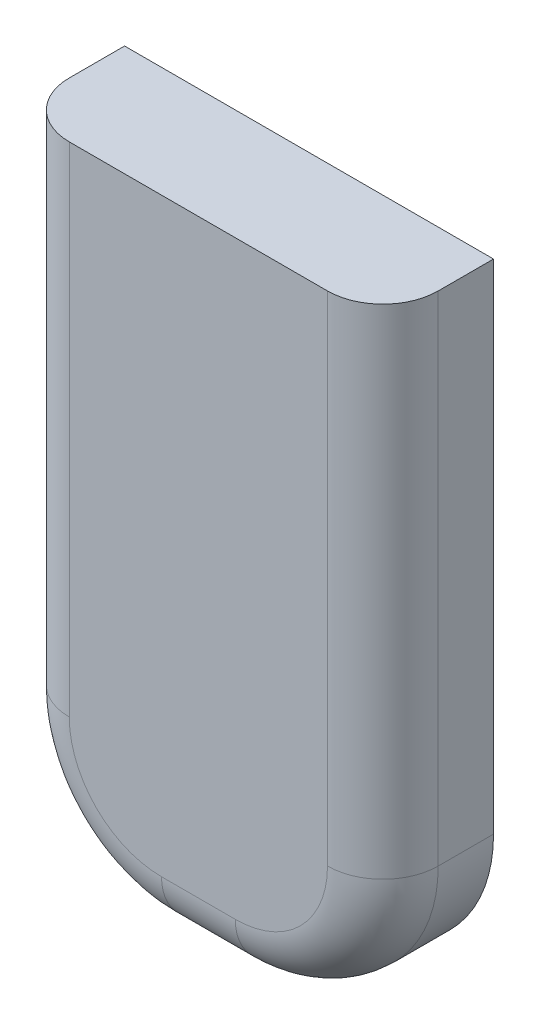
SolidWorks part; units mm, degrees
ref_plane "Front Plane" through (0, 0, 0) normal (0, 0, 1) x (1, 0, 0)
ref_plane "Top Plane" through (0, 0, 0) normal (0, 1, 0) x (1, 0, 0)
ref_plane "Right Plane" through (0, 0, 0) normal (1, 0, 0) x (0, 0, -1)
sketch "Sketch1" plane through (0, 0, 0) normal (0, 0, 1) x (1, 0, 0)
  line L0 (18.5859, -140) -> (118.5859, -140) construction
  line L1 (58.5859, -125) -> (78.5859, -125)
  line L2 (58.5859, -125) -> (58.5859, -152)
  line L3 (66.5859, -160) -> (70.5859, -160)
  line L4 (78.5859, -125) -> (78.5859, -152)
  line L5 (68.5859, -300) -> (68.5859, -140) construction
  line L6 (63.5859, -300) -> (73.5859, -300) construction
  arc A0 (70.5859, -160) -> (78.5859, -152) centre (70.5859, -152) ccw
  arc A1 (58.5859, -152) -> (66.5859, -160) centre (66.5859, -152) ccw
  point P16 (58.5859, -160)
  dimension "D5" = 8
  dimension "D1" = 35
  dimension "D2" = 20
  dimension "D3" = 10
  dimension "D4" = 15
extrude "Boss-Extrude1" add sketch "Sketch1" along normal blind 6
fillet "Fillet1" radius 3 5 edges at (58.5859, -138.5, 6) (78.5859, -138.5, 6) (76.2427, -157.6569, 6) (68.5859, -160, 6) (60.929, -157.6569, 6)
sketch "Sketch2" plane through (0, 0, 0) normal (0, 0, -1) x (-1, 0, 0)
  circle A0 centre (-68.5859, -149) radius 7.5
extrude "Cut-Extrude1" cut sketch "Sketch2" against normal blind 4
